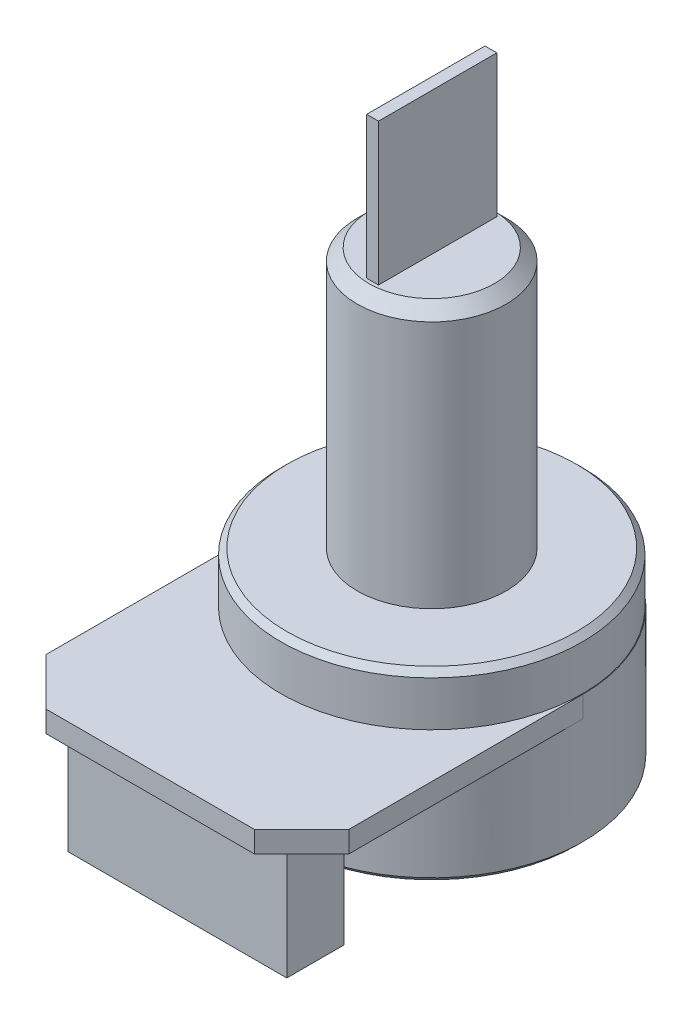
SolidWorks part; units mm, degrees
ref_plane "Front Plane" through (0, 0, 0) normal (0, 0, 1) x (1, 0, 0)
ref_plane "Top Plane" through (0, 0, 0) normal (0, 1, 0) x (1, 0, 0)
ref_plane "Right Plane" through (0, 0, 0) normal (1, 0, 0) x (0, 0, -1)
sketch "Sketch1" plane through (0, 0, 0) normal (0, 1, 0) x (1, 0, 0)
  circle A0 centre (0, 0) radius 12.8
  dimension "D1" = 25.6
extrude "Boss-Extrude1" add sketch "Sketch1" along normal blind 9.5
sketch "Sketch2" plane through (0, 9.5, 0) normal (0, 1, 0) x (1, 0, 0)
  line L1 (-1002.0502, 12.8) -> (48997.9498, 12.8) construction
  line L2 (12.8, -23.8) -> (-12.8, -23.8)
  line L3 (12.8, -23.8) -> (12.8, 0)
  line L4 (12.8, 0) -> (-12.8, 0) construction
  line L5 (-12.8, -23.8) -> (-12.8, 0)
  line L6 (12.8, -23.8) -> (-12.8, 0) construction
  line L7 (12.8, 0) -> (-12.8, -23.8) construction
  circle A1 centre (0, 0) radius 12.8 construction
  arc A2 (-12.8, 0) -> (12.8, 0) centre (0, 0) cw
  point P6 (0, -11.9)
  dimension "D1" = 36.6
extrude "Boss-Extrude2" add sketch "Sketch2" along normal blind 1.8
sketch "Sketch3" plane through (0, 11.3, 0) normal (0, 1, 0) x (1, 0, 0)
  circle A0 centre (0, 0) radius 12.75
  dimension "D1" = 25.5
extrude "Boss-Extrude3" add sketch "Sketch3" along normal offset from surface (4.3 mm away) 15.6 up to face at (0, 0, 12.8)
sketch "Sketch4" plane through (0, 15.6, 0) normal (0, 1, 0) x (1, 0, 0)
  circle A0 centre (0, 0) radius 6.3
  dimension "D1" = 12.6
extrude "Boss-Extrude4" add sketch "Sketch4" along normal offset from surface (22 mm away) 37.6 up to face at (0, 0, 12.8)
chamfer "Chamfer1" distance 1 angle 45 1 edges at (0, 37.6, 6.3)
chamfer "Chamfer2" distance 0.5 angle 45 2 edges at (0, 15.6, 12.75) (0, 0, 12.8)
sketch "Sketch5" plane through (0, 9.5, 0) normal (0, -1, 0) x (1, 0, 0)
  line L1 (9.2577, 16.6827) -> (-9.2577, 16.6827)
  line L2 (9.2577, 16.6827) -> (9.2577, 21.5128)
  line L3 (9.2577, 21.5128) -> (-9.2577, 21.5128)
  line L4 (-9.2577, 16.6827) -> (-9.2577, 21.5128)
  line L5 (9.2577, 16.6827) -> (-9.2577, 21.5128) construction
  line L6 (9.2577, 21.5128) -> (-9.2577, 16.6827) construction
  point P0 (0, 19.0978)
extrude "Boss-Extrude5" add sketch "Sketch5" along normal blind 10
sketch "Sketch6" plane through (0, 37.6, 0) normal (0, 1, 0) x (1, 0, 0)
  line L1 (-0.5, -5) -> (0.5, -5)
  line L2 (-0.5, -5) -> (-0.5, 5)
  line L3 (-0.5, 5) -> (0.5, 5)
  line L4 (0.5, -5) -> (0.5, 5)
  line L5 (-0.5, -5) -> (0.5, 5) construction
  line L6 (-0.5, 5) -> (0.5, -5) construction
  point P0 (0, 0)
  dimension "D1" = 1
  dimension "D2" = 10
extrude "Boss-Extrude6" add sketch "Sketch6" along normal blind 12
chamfer "Chamfer3" distance 4 angle 45 2 edges at (-12.8, 10.4, 23.8) (12.8, 10.4, 23.8)
